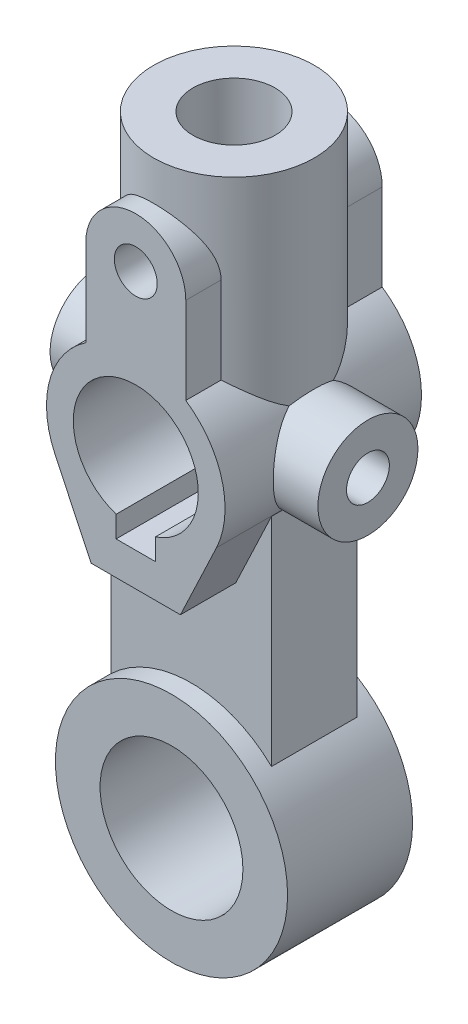
SolidWorks part; units mm, degrees
ref_plane "Front Plane" through (0, 0, 0) normal (0, 0, 1) x (1, 0, 0)
ref_plane "Top Plane" through (0, 0, 0) normal (0, 1, 0) x (1, 0, 0)
ref_plane "Right Plane" through (0, 0, 0) normal (1, 0, 0) x (0, 0, -1)
sketch "Sketch1" plane through (0, 0, 0) normal (0, 0, 1) x (1, 0, 0)
  line L0 (0, 0) -> (0, -95) construction
  circle A0 centre (0, -95) radius 20
  circle A1 centre (0, -95) radius 32.5
  dimension "D2" = 65
  dimension "D3" = 40
  dimension "D1" = 95
extrude "Extrude1" add sketch "Sketch1" along normal mid plane 35
sketch "Sketch2" plane through (0, 0, 0) normal (0, 1, 0) x (1, 0, 0)
  line L1 (-22.5, -12) -> (22.5, -12)
  line L2 (-22.5, -12) -> (-22.5, 12)
  line L3 (-22.5, 12) -> (22.5, 12)
  line L4 (22.5, -12) -> (22.5, 12)
  line L5 (-22.5, -12) -> (22.5, 12) construction
  line L6 (-22.5, 12) -> (22.5, -12) construction
  point P0 (0, 0)
  dimension "D1" = 24
  dimension "D2" = 45
extrude "Extrude2" add sketch "Sketch2" against normal up to next
sketch "Sketch3" plane through (0, 0, 0) normal (0, 1, 0) x (1, 0, 0)
  circle A0 centre (0, 0) radius 22.5
  dimension "D2" = 45
extrude "Extrude3" add sketch "Sketch3" along normal blind 70
sketch "Sketch4" plane through (0, 0, 0) normal (0, 0, 1) x (1, 0, 0)
  line L0 (-12.5, -32) -> (12.5, -32)
  line L1 (-12.5, -32) -> (-22.5914, -10.7065)
  line L2 (-14, 20.7123) -> (-14, 45)
  line L3 (14, 45) -> (14, 20.7123)
  line L4 (12.5, -32) -> (22.5914, -10.7065)
  arc A0 (-22.5914, -10.7065) -> (-14, 20.7123) centre (0, 0) cw
  arc A1 (-14, 45) -> (14, 45) centre (0, 45) cw
  arc A2 (22.5914, -10.7065) -> (14, 20.7123) centre (0, 0) ccw
  point P11 (0, -32)
  dimension "D2" = 45
  dimension "D4" = 14
  dimension "D5" = 25
  dimension "D1" = 32
  dimension "D3" = 25
extrude "Extrude4" add sketch "Sketch4" along normal mid plane 55
sketch "Sketch5" plane through (0, 0, 0) normal (1, 0, 0) x (0, 0, -1)
  circle A0 centre (0, 0) radius 14
  dimension "D1" = 28
extrude "Extrude5" add sketch "Sketch5" along normal mid plane 75
sketch "Sketch6" plane through (37.5, 0, 0) normal (1, 0, 0) x (0, 0, -1)
  circle A0 centre (0, 0) radius 6
  dimension "D1" = 12
extrude "Extrude6" cut sketch "Sketch6" against normal through all
sketch "Sketch7" plane through (0, 0, 27.5) normal (0, 0, 1) x (1, 0, 0)
  circle A0 centre (0, 45) radius 6
  dimension "D1" = 12
extrude "Extrude7" cut sketch "Sketch7" against normal through all
sketch "Sketch8" plane through (0, 0, 27.5) normal (0, 0, 1) x (1, 0, 0)
  line L0 (-5.5, -16.6132) -> (-5.5, -22.6132)
  line L1 (-5.5, -22.6132) -> (5.5, -22.6132)
  line L2 (5.5, -22.6132) -> (5.5, -16.6132)
  arc A0 (5.5, -16.6132) -> (-5.5, -16.6132) centre (0, 0) ccw
  point P1 (0, -22.6132)
  dimension "D1" = 35
  dimension "D2" = 11
  dimension "D3" = 6
extrude "Extrude8" cut sketch "Sketch8" against normal through all
sketch "Sketch9" plane through (0, 0, 0) normal (0, 1, 0) x (1, 0, 0)
  circle A0 centre (0, 0) radius 11.5
  dimension "D1" = 23
extrude "Extrude9" cut sketch "Sketch9" along normal through all
